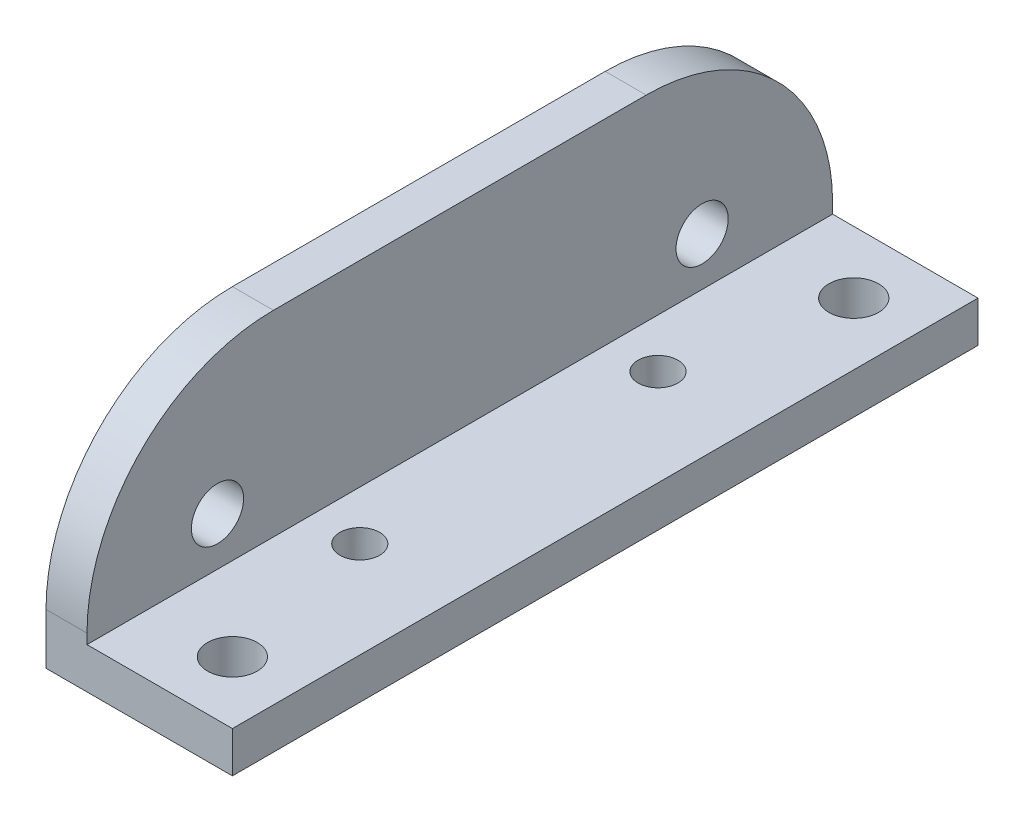
SolidWorks part; units mm, degrees
ref_plane "Front Plane" through (0, 0, 0) normal (0, 0, 1) x (1, 0, 0)
ref_plane "Top Plane" through (0, 0, 0) normal (0, 1, 0) x (1, 0, 0)
ref_plane "Right Plane" through (0, 0, 0) normal (1, 0, 0) x (0, 0, -1)
sketch "Sketch1" plane through (0, 0, 0) normal (0, 0, 1) x (1, 0, 0)
  line L0 (0, 0) -> (0, 19.1)
  line L1 (0, 19.1) -> (3.3, 19.1)
  line L2 (3.3, 19.1) -> (3.3, 3.3)
  line L3 (3.3, 3.3) -> (19.1, 3.3)
  line L4 (19.1, 3.3) -> (19.1, 0)
  line L5 (19.1, 0) -> (0, 0)
  dimension "D1" = 19.1
  dimension "D2" = 19.1
  dimension "D3" = 3.3
  dimension "D4" = 3.3
extrude "Extrude1" add sketch "Sketch1" along normal mid plane 60
sketch "Sketch2" plane through (0, 0, 0) normal (0, -1, 0) x (1, 0, 0)
  line L0 (0, -30) -> (19.1, -30) construction
  line L1 (19.1, 30) -> (15, 30)
  line L2 (19.1, 30) -> (19.1, -30)
  line L3 (19.1, -30) -> (15, -30)
  line L4 (15, 30) -> (15, -30)
  line L5 (0, 30) -> (0, -30) construction
  dimension "D1" = 15
extrude "Cut for walker chassis" cut sketch "Sketch2" against normal through all
hole_wizard "Ø4.2 (4.2) Diameter Hole1" positions "Sketch4" profile "Sketch3" hole size "Ø4.2" standard "Ansi Metric" end condition through all
sketch "Sketch4" plane through (0, 0, 0) normal (-1, 0, 0) x (0, 0, 1)
  line L0 (30, 0) -> (-30, 0) construction
  point P0 (-19.5, 7.18)
  point P1 (19.5, 7.18)
  dimension "D1" = 39
  dimension "D2" = 19.5
  dimension "D3" = 7.18
sketch "Sketch3" plane through (0, 7.18, -19.5) normal (0, 1, 0) x (0, 0, 1)
  line L0 (0, 0) -> (0, 15)
  line L1 (0, 15) -> (2.1, 15)
  line L2 (2.1, 15) -> (2.1, 0)
  line L5 (2.1, 0) -> (0, 0)
  line L11 (0, -6.35) -> (0, 107.95) construction
  dimension "Thru Hole Dia." = 4.2
  dimension "Thru Hole Depth" = 15
hole_wizard "M4x0.7 Tapped Hole1" positions "Sketch6" profile "Sketch5" tap size "M4x0.7" standard "Ansi Metric" end condition up to next
sketch "Sketch6" plane through (0, 0, 0) normal (0, -1, 0) x (1, 0, 0)
  line L0 (0, -30) -> (15, -30) construction
  line L1 (0, 30) -> (15, 30) construction
  line L2 (15, 30) -> (15, -30) construction
  point P0 (10, 25)
  point P1 (10, -25)
  dimension "D1" = 5
  dimension "D2" = 5
  dimension "D3" = 5
sketch "Sketch5" plane through (10, 0, 25) normal (1, 0, 0) x (0, 0, -1)
  line L0 (0, 0) -> (0, 3.3)
  line L1 (0, 3.3) -> (2, 3.3)
  line L2 (2, 3.3) -> (2, 0)
  line L5 (2, 0) -> (0, 0)
  line L11 (0, -6.35) -> (0, 107.95) construction
  dimension "Thread Major Dia." = 4
  dimension "Thru Tap Drill Depth" = 3.3
sketch "Sketch7" plane through (0, 0, 0) normal (0, -1, 0) x (1, 0, 0)
  line L0 (-4.1016, 0) -> (20.1367, 0) construction
  line L1 (0, 30) -> (0, -30) construction
  circle A2 centre (7.25, -12) radius 1.6
  circle A3 centre (7.25, 12) radius 1.6
  dimension "D1" = 3.2
  dimension "D2" = 12
  dimension "D3" = 24
  dimension "D4" = 7.25
extrude "Cut-Extrude1" cut sketch "Sketch7" against normal through all
sketch "Эскиз3" plane through (0, 0, 0) normal (1, 0, 0) x (0, 0, -1)
  line L0 (-30, 19.1) -> (-30, 4.1)
  line L1 (-30, 19.1) -> (-30, 0) construction
  line L2 (-30, 19.1) -> (-15, 19.1)
  line L3 (-30, 19.1) -> (30, 19.1) construction
  arc A1 (-15, 19.1) -> (-30, 4.1) centre (-15, 4.1) ccw
  dimension "D1" = 15
  dimension "D2" = 15
sketch "Эскиз4" plane through (0, 0, 0) normal (1, 0, 0) x (0, 0, -1)
  line L0 (0, 20.5216) -> (0, -8.7793) construction
  point P3 (0, 0)
extrude "Вырез-Вытянуть2" cut sketch "Эскиз3" along normal blind 10 contours A1 L0 L2
mirror "Зеркальное отражение1" about plane through (0, 0, 0) normal (0, 0, 1) of "Вырез-Вытянуть2"
